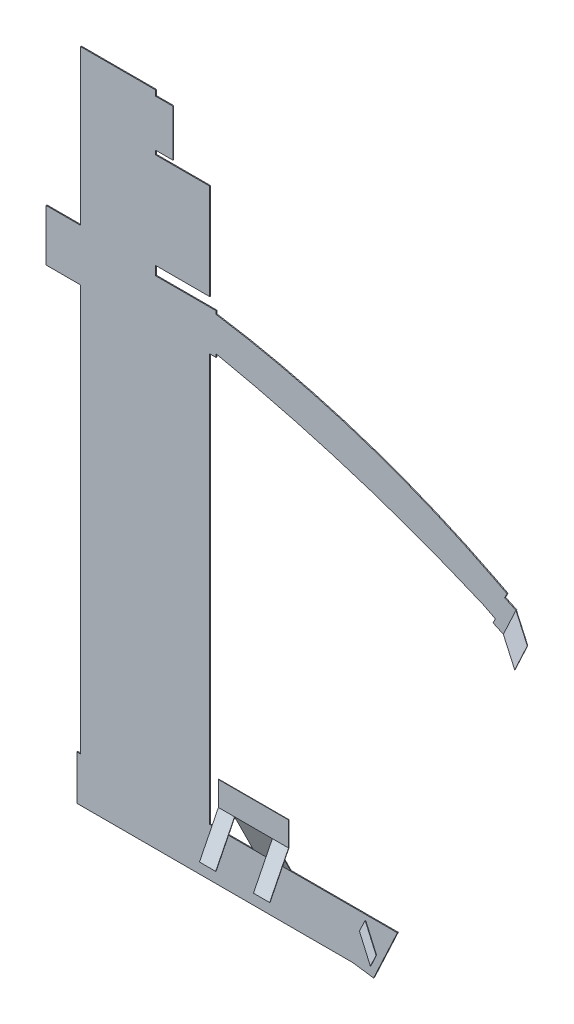
SolidWorks part; units mm, degrees
ref_plane "前视基准面" through (0, 0, 0) normal (0, 0, 1) x (1, 0, 0)
ref_plane "上视基准面" through (0, 0, 0) normal (0, 1, 0) x (1, 0, 0)
ref_plane "右视基准面" through (0, 0, 0) normal (1, 0, 0) x (0, 0, -1)
ref_plane "基准面4"
sketch "草图1" plane through (0, 0, 0) normal (0, 0, 1) x (1, 0, 0)
  line L0 (849.2, -450.2) -> (849.2, -502.2)
  line L1 (849.2, -502.2) -> (868.2, -502.2)
  line L2 (868.2, -502.2) -> (868.2, -450.2)
  line L3 (868.2, -450.2) -> (849.2, -450.2)
  line L4 (765.5, -1125.1) -> (761.5, -1125.1)
  line L5 (761.5, -1125.1) -> (761.5, -1174.6)
  line L6 (761.5, -1174.6) -> (765.5, -1174.6)
  line L7 (765.5, -1174.6) -> (825.5, -1174.6)
  line L8 (825.5, -1174.6) -> (825.5, -1125.1)
  line L9 (825.5, -1125.1) -> (765.5, -1125.1)
  line L10 (909.2, -1091.6) -> (909.2, -1064)
  line L11 (909.2, -1064) -> (849.2, -1064)
  line L12 (849.2, -1064) -> (849.2, -1121.1)
  line L13 (849.2, -1121.1) -> (909.2, -1121.1)
  line L14 (909.2, -1121.1) -> (909.2, -1091.6)
  line L15 (765.5, -504.2) -> (825.5, -504.2)
  line L16 (825.5, -504.2) -> (825.5, -444.2)
  line L17 (825.5, -444.2) -> (765.5, -444.2)
  line L18 (765.5, -444.2) -> (765.5, -504.2)
  line L19 (849.2, -506.7) -> (849.2, -613.1)
  line L20 (849.2, -613.1) -> (909.2, -613.1)
  line L21 (909.2, -613.1) -> (909.2, -506.7)
  line L22 (909.2, -506.7) -> (849.2, -506.7)
  line L23 (849.2, -1050.1) -> (849.2, -1064)
  line L24 (849.2, -1064) -> (909.2, -1064)
  line L25 (909.2, -1064) -> (909.2, -953.1)
  line L26 (909.2, -953.1) -> (849.2, -953.1)
  line L27 (849.2, -953.1) -> (849.2, -1050.1)
  line L28 (765.5, -897.6) -> (765.5, -1008.6)
  line L29 (765.5, -1008.6) -> (825.5, -1008.6)
  line L30 (825.5, -1008.6) -> (825.5, -897.6)
  line L31 (825.5, -897.6) -> (765.5, -897.6)
  line L32 (765.5, -786.6) -> (765.5, -897.6)
  line L33 (765.5, -897.6) -> (825.5, -897.6)
  line L34 (825.5, -897.6) -> (825.5, -786.6)
  line L35 (825.5, -786.6) -> (765.5, -786.6)
  line L36 (909.2, -841.8) -> (849.2, -841.8)
  line L37 (849.2, -841.8) -> (849.2, -953.1)
  line L38 (849.2, -953.1) -> (909.2, -953.1)
  line L39 (909.2, -953.1) -> (909.2, -841.8)
  line L40 (765.5, -616.2) -> (825.5, -616.2)
  line L41 (825.5, -616.2) -> (825.5, -504.2)
  line L42 (825.5, -504.2) -> (765.5, -504.2)
  line L43 (765.5, -504.2) -> (765.5, -616.2)
  line L44 (765.5, -673.6) -> (765.5, -786.6)
  line L45 (765.5, -786.6) -> (825.5, -786.6)
  line L46 (825.5, -786.6) -> (825.5, -673.6)
  line L47 (825.5, -673.6) -> (765.5, -673.6)
  line L48 (765.5, -1008.6) -> (765.5, -1125.1)
  line L49 (765.5, -1125.1) -> (825.5, -1125.1)
  line L50 (825.5, -1125.1) -> (825.5, -1008.6)
  line L51 (825.5, -1008.6) -> (765.5, -1008.6)
  line L52 (909.2, -710.2) -> (849.2, -710.2)
  line L53 (849.2, -710.2) -> (849.2, -841.8)
  line L54 (849.2, -841.8) -> (909.2, -841.8)
  line L55 (909.2, -841.8) -> (909.2, -710.2)
  line L56 (849.2, -1174.6) -> (1031.2, -1174.6)
  line L57 (1031.2, -1174.6) -> (1031.2, -1121.1)
  line L58 (1031.2, -1121.1) -> (909.2, -1121.1)
  line L59 (909.2, -1121.1) -> (849.2, -1121.1)
  line L60 (849.2, -1121.1) -> (849.2, -1174.6)
  line L61 (849.2, -623.1) -> (849.2, -668.1)
  line L62 (849.2, -668.1) -> (849.2, -681.1)
  line L63 (849.2, -681.1) -> (849.2, -710.2)
  line L64 (849.2, -710.2) -> (909.2, -710.2)
  line L65 (909.2, -710.2) -> (909.2, -668.1)
  line L66 (909.2, -668.1) -> (916.2, -668.1)
  line L67 (916.2, -668.1) -> (916.2, -664.6)
  line L68 (1213.4, -757.7) -> (1226.4, -727)
  line L69 (916.2, -626.6) -> (916.2, -623.1)
  line L70 (916.2, -623.1) -> (849.2, -623.1)
  line L71 (727.5, -616.2) -> (727.5, -673.6)
  line L72 (727.5, -673.6) -> (765.5, -673.6)
  line L73 (765.5, -673.6) -> (825.5, -673.6)
  line L74 (825.5, -673.6) -> (825.5, -786.6)
  line L75 (825.5, -786.6) -> (825.5, -897.6)
  line L76 (825.5, -897.6) -> (825.5, -1008.6)
  line L77 (825.5, -1008.6) -> (825.5, -1125.1)
  line L78 (825.5, -1125.1) -> (825.5, -1174.6)
  line L79 (825.5, -1174.6) -> (849.2, -1174.6)
  line L80 (849.2, -1174.6) -> (849.2, -1121.1)
  line L81 (849.2, -1121.1) -> (849.2, -1064)
  line L82 (849.2, -1064) -> (849.2, -1050.1)
  line L83 (849.2, -1050.1) -> (849.2, -953.1)
  line L84 (849.2, -953.1) -> (849.2, -841.8)
  line L85 (849.2, -841.8) -> (849.2, -710.2)
  line L86 (849.2, -710.2) -> (849.2, -681.1)
  line L87 (849.2, -681.1) -> (849.2, -668.1)
  line L88 (849.2, -668.1) -> (849.2, -623.1)
  line L89 (849.2, -623.1) -> (849.2, -613.1)
  line L90 (849.2, -613.1) -> (849.2, -506.7)
  line L91 (849.2, -506.7) -> (849.2, -502.2)
  line L92 (849.2, -502.2) -> (849.2, -450.2)
  line L93 (849.2, -450.2) -> (849.2, -444.2)
  line L94 (849.2, -444.2) -> (825.5, -444.2)
  line L95 (825.5, -444.2) -> (825.5, -504.2)
  line L96 (825.5, -504.2) -> (825.5, -616.2)
  line L97 (825.5, -616.2) -> (765.5, -616.2)
  line L98 (765.5, -616.2) -> (727.5, -616.2)
  arc A0 (1213.4, -757.7) -> (916.2, -664.6) centre (605.6007, -2177.0365) ccw
  arc A1 (1226.4, -727) -> (916.2, -626.6) centre (761.993, -1632.4479) ccw
  dimension "D33" = 1017.6
  dimension "D36" = 1544
  dimension "D1" = 38
  dimension "D2" = 60
  dimension "D3" = 112
  dimension "D4" = 60
  dimension "D5" = 60
  dimension "D6" = 23.7
  dimension "D7" = 6
  dimension "D8" = 19
  dimension "D9" = 52
  dimension "D10" = 4.5
  dimension "D11" = 60
  dimension "D12" = 106.4
  dimension "D13" = 113
  dimension "D14" = 60
  dimension "D15" = 111
  dimension "D16" = 111
  dimension "D17" = 60
  dimension "D18" = 116.5
  dimension "D19" = 60
  dimension "D20" = 49.5
  dimension "D21" = 23.7
  dimension "D22" = 10
  dimension "D23" = 67
  dimension "D24" = 3.5
  dimension "D25" = 45
  dimension "D26" = 3.5
  dimension "D27" = 13
  dimension "D28" = 369
  dimension "D29" = 29.5
  dimension "D30" = 182
  dimension "D31" = 326.0432
  dimension "D32" = 326.0432
  dimension "D34" = 311.4409
  dimension "D35" = 311.4409
  dimension "D37" = 53.5
  dimension "D38" = 42.1
  dimension "D39" = 131.6
  dimension "D40" = 111.3
  dimension "D41" = 110.9
  dimension "D42" = 4
extrude "拉伸1" add sketch "草图1" against normal blind 1 contours L2 L3 L0 L1 | L8 L9 L4 L5 L6 L7 | L13 L14 L10 L11 L12 | L17 L18 L15 L16 | L21 L22 L19 L20 | L26 L27 L23 L11 L25 | L30 L31 L28 L29 | L34 L35 L32 L31 | L26 L39 L36 L37 | L15 L43 L40 L41 | L46 L47 L44 L35 | L9 L50 L29 L48 | L36 L55 L52 L53 | L13 L60 L56 L57 L58 | L68 A1 L69 L70 L61 L62 L63 L52 L65 L66 L67 A0 | L40 L98 L71 L72 L47 L46 L34 L30 L50 L8 L79 L60 L12 L23 L27 L37 L53 L63 L62 L61 L89 L19 L91 L0 L93 L94 L16 L41
ref_plane "基准面5" through (0, 0, 0) normal (0, 0, 1) x (1, 0, 0)
sketch "草图2" plane through (0, 0, 0) normal (0, 0, 1) x (1, 0, 0)
  line L0 (1237.0998, -739.0064) -> (1239.7468, -733.8456)
  line L1 (1239.7468, -733.8456) -> (1226.4, -727)
  line L2 (1226.4, -727) -> (1213.4, -757.7)
  line L3 (1213.4, -757.7) -> (1226.7468, -764.5456)
  line L4 (1226.7468, -764.5456) -> (1224.1478, -769.6129)
  line L5 (1224.1478, -769.6129) -> (1235.5455, -774.9277)
  line L6 (1235.5455, -774.9277) -> (1249.5818, -744.8268)
  line L7 (1249.5818, -744.8268) -> (1237.0998, -739.0064)
extrude "拉伸2" add sketch "草图2" against normal blind 1
sketch "草图3" plane through (-76.1385, -163.2795, 0) normal (-0.4226, -0.9063, 0) x (0.9063, -0.4226, 0)
  line L0 (1447.2831, 0) -> (1477.7831, 15)
  line L1 (1477.7831, 15) -> (1477.7831, 14.5)
  line L2 (1477.7831, 14.5) -> (1447.2831, -0.5)
  line L3 (1447.2831, -0.5) -> (1447.2831, 0)
  dimension "D1" = 30.5
extrude "拉伸3" add sketch "草图3" against normal up to surface (33.2127 mm away) up to face at (1243.3408, -741.9166, -0.5)
ref_plane "基准面6" through (999.7, -1174.6, 0) normal (1, 0, 0) x (0, 0, -1)
sketch "草图4" plane through (999.7, -1174.6, 0) normal (1, 0, 0) x (0, 0, -1)
  line L0 (-20.3587, 95.5) -> (-20.3587, 122.5)
  line L1 (-20.3587, 122.5) -> (-20.8587, 122.5)
  line L2 (-20.8587, 122.5) -> (-20.8587, 95.5)
  line L3 (-20.8587, 95.5) -> (-20.3587, 95.5)
  line L4 (0.5, 53.5) -> (-20.3587, 95.5)
  line L5 (-20.3587, 95.5) -> (-20.8587, 95.5)
  line L6 (-20.8587, 95.5) -> (0, 53.5)
  line L7 (0, 53.5) -> (0.5, 53.5)
  line L8 (1, 53.5) -> (0, 53.5) construction
  line L9 (1, 53.5) -> (0, 53.5)
  dimension "D1" = 42
  dimension "D2" = 27
  dimension "D3" = 0.5
extrude "拉伸4" add sketch "草图4" against normal blind 42 contours L2 L3 L0 L1 | L6 L7 L4 L3
ref_plane "基准面7" through (999.7, -1174.6, 0) normal (1, 0, 0) x (0, 0, -1)
sketch "草图5" plane through (999.7, -1174.6, 0) normal (1, 0, 0) x (0, 0, -1)
  line L0 (-20.3587, 122.5) -> (-20.8587, 122.5)
  line L1 (-20.8587, 122.5) -> (-20.8587, 95.5)
  line L2 (-20.8587, 95.5) -> (-20.3587, 95.5)
  line L3 (-20.3587, 95.5) -> (-20.3587, 122.5)
  line L4 (-20.8587, 95.5) -> (-41.8587, 53.5)
  line L5 (-41.8587, 53.5) -> (-41.3587, 53.5)
  line L6 (-41.3587, 53.5) -> (-20.3587, 95.5)
  line L7 (-20.3587, 95.5) -> (-20.8587, 95.5)
  line L8 (-20.3587, 122.5) -> (-20.8587, 122.5) construction
  dimension "D1" = 46.9574
  dimension "D2" = 46.9574
extrude "拉伸5" add sketch "草图5" along normal blind 18 contours L2 L3 L0 L1 | L5 L6 L2 L4
ref_plane "基准面8" through (978.7, -1174.6, 0) normal (-1, 0, 0) x (0, 0, 1)
mirror "镜像1" about plane through (978.7, -1174.6, 0) normal (-1, 0, 0) of "拉伸5"
ref_plane "基准面9" through (0, 0, 0) normal (0, 0, 1) x (1, 0, 0)
sketch "草图6" plane through (0, 0, 0) normal (0, 0, 1) x (1, 0, 0)
  line L0 (1031.2, -1121.1) -> (1117.8, -1121.1)
  line L1 (1117.8, -1121.1) -> (1091.3363, -1177.8516)
  line L2 (1091.3363, -1177.8516) -> (1068.2, -1174.6)
  line L3 (1068.2, -1174.6) -> (1031.2, -1174.6)
  line L4 (1031.2, -1174.6) -> (1031.2, -1121.1)
extrude "拉伸6" add sketch "草图6" against normal blind 1
ref_plane "基准面10" through (1109.1363, -1139.6793, 0) normal (-0.4226, -0.9063, 0) x (0.9063, -0.4226, 0)
sketch "草图7" plane through (1109.1363, -1139.6793, 0) normal (-0.4226, -0.9063, 0) x (0.9063, -0.4226, 0)
  line L0 (-30, -0.5) -> (0, 14.5)
  line L1 (0, 14.5) -> (0, 15)
  line L2 (0, 15) -> (-30, 0)
  line L3 (-30, 0) -> (-30, -0.5)
  dimension "D1" = 30
  dimension "D3" = 0.5
  dimension "D4" = 0.5
extrude "拉伸7" add sketch "草图7" along normal blind 15
